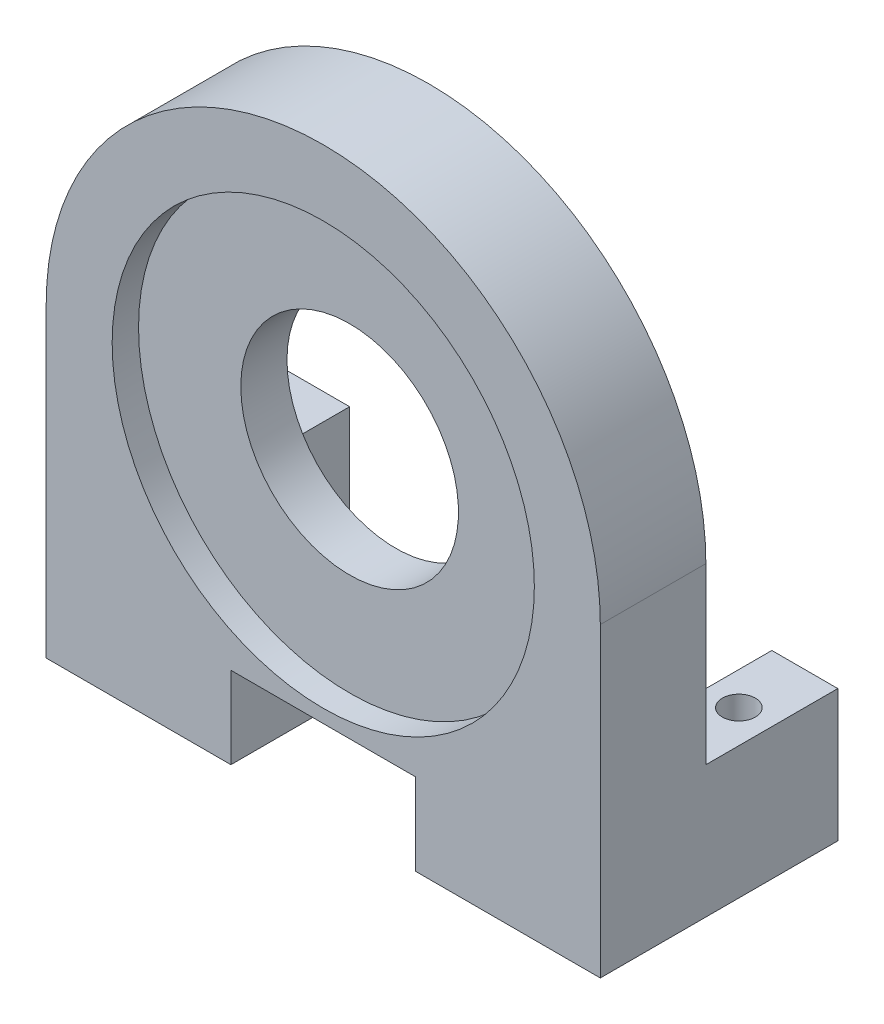
SolidWorks part; units mm, degrees
ref_plane "Front Plane" through (0, 0, 0) normal (0, 0, 1) x (1, 0, 0)
ref_plane "Top Plane" through (0, 0, 0) normal (0, 1, 0) x (1, 0, 0)
ref_plane "Right Plane" through (0, 0, 0) normal (1, 0, 0) x (0, 0, -1)
sketch "Sketch2" plane through (0, 0, 0) normal (0, 0, 1) x (1, 0, 0)
  line L0 (-21, 0) -> (21, 0)
  line L1 (-21, 0) -> (-21, 23.2)
  line L2 (21, 23.2) -> (21, 0)
  circle A1 centre (0, 23.2) radius 16
  arc A3 (-21, 23.2) -> (21, 23.2) centre (0, 23.2) cw
  point P2 (0, 44.2)
  point P5 (0, 0)
  point P7 (0, 0)
  point P8 (0, 0.9)
  point P11 (0, 23.2)
  point P12 (0, 39.2)
  dimension "D1" = 32
  dimension "D2" = 21
  dimension "D3" = 23.2
  dimension "D4" = 42
extrude "Boss-Extrude1" add sketch "Sketch2" along normal mid plane 8
sketch "Sketch3" plane through (0, 0, 0) normal (0, 0, 1) x (1, 0, 0)
  circle A1 centre (0, 23.2) radius 8.25
  circle A2 centre (0, 23.2) radius 16 construction
  circle A3 centre (0, 23.2) radius 16
  dimension "D1" = 16.5
extrude "Boss-Extrude2" add sketch "Sketch3" against normal blind 1.5 and the other way offset from surface (2 mm away) 2 other way up to face at (0, 16.85, 4)
sketch "Sketch6" plane through (0, 0, -4) normal (0, 0, -1) x (-1, 0, 0)
  line L0 (0, 18.7908) -> (0, -15.548) construction
  line L1 (-21, 0) -> (-16, 0)
  line L2 (-21, 0) -> (-21, 10)
  line L3 (-21, 10) -> (-16, 10)
  line L4 (-16, 0) -> (-16, 10)
  line L5 (21, 0) -> (21, 10)
  line L6 (21, 0) -> (16, 0)
  line L7 (16, 0) -> (16, 10)
  line L8 (21, 10) -> (16, 10)
  dimension "D1" = 5
  dimension "D2" = 10
extrude "Boss-Extrude4" add sketch "Sketch6" along normal blind 10
sketch "Sketch7" plane through (0, 0, 0) normal (0, -1, 0) x (1, 0, 0)
  line L0 (0, 9.1446) -> (0, -14.4574) construction
  line L1 (-16, -14) -> (-21, -14) construction
  line L2 (-21, 4) -> (-21, -14) construction
  line L3 (-21, 4) -> (21, 4) construction
  circle A0 centre (-18.5, -9) radius 1.25
  circle A1 centre (18.5, -9) radius 1.25
  circle A2 centre (-18.5, -1) radius 1.25
  circle A3 centre (18.5, -1) radius 1.25
  dimension "D1" = 2.5
  dimension "D4" = 5
  dimension "D2" = 5
  dimension "D3" = 2.5
extrude "Cut-Extrude2" cut sketch "Sketch7" against normal up to surface (10 mm away) up to face at (-18.5, 10, -9)
sketch "Sketch8" plane through (0, 0, -4) normal (0, 0, -1) x (-1, 0, 0)
  line L0 (-7, -6.2) -> (-7, 6.2)
  line L1 (-7, -6.2) -> (7, -6.2)
  line L2 (-7, 6.2) -> (7, 6.2)
  line L3 (7, -6.2) -> (7, 6.2)
  line L4 (-7, -6.2) -> (7, 6.2) construction
  line L5 (-7, 6.2) -> (7, -6.2) construction
  circle A0 centre (0, 23.2) radius 16 construction
  point P0 (0, 7.2)
  point P9 (0, 0)
  dimension "D1" = 1
  dimension "D2" = 14
extrude "Cut-Extrude3" cut sketch "Sketch8" against normal through all
